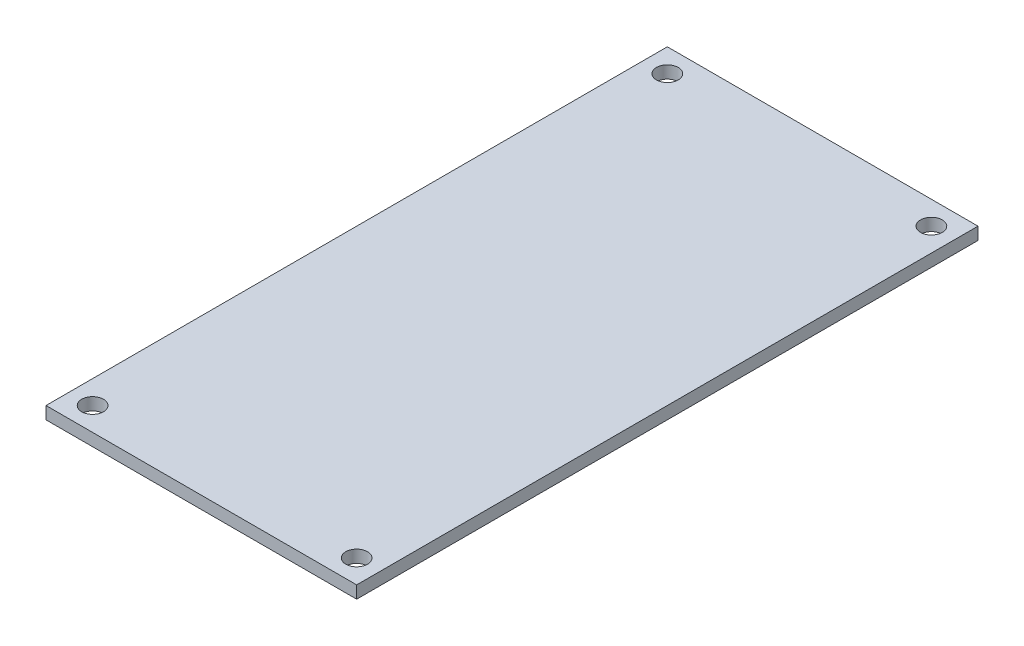
SolidWorks part; units mm, degrees
ref_plane "정면" through (0, 0, 0) normal (0, 0, 1) x (1, 0, 0)
ref_plane "윗면" through (0, 0, 0) normal (0, 1, 0) x (1, 0, 0)
ref_plane "우측면" through (0, 0, 0) normal (1, 0, 0) x (0, 0, -1)
sketch "스케치1" plane through (0, 0, 0) normal (0, 1, 0) x (1, 0, 0)
  line L0 (0, 50) -> (0, -50) construction
  line L5 (25, -50) -> (-25, -50)
  line L6 (25, -50) -> (25, 50)
  line L7 (25, 50) -> (-25, 50)
  line L8 (-25, -50) -> (-25, 50)
  line L9 (25, -50) -> (-25, 50) construction
  line L10 (25, 50) -> (-25, -50) construction
  line L11 (-25, 0) -> (25, 0) construction
  circle A0 centre (-21.25, 46.25) radius 1.75
  circle A1 centre (21.25, 46.25) radius 1.75
  circle A2 centre (21.25, -46.25) radius 1.75
  circle A3 centre (-21.25, -46.25) radius 1.75
  point P0 (0, 0)
  dimension "D3" = 3.5
  dimension "D1" = 50
  dimension "D2" = 100
  dimension "D4" = 3.75
  dimension "D5" = 3.75
extrude "보스-돌출1" add sketch "스케치1" along normal blind 2
